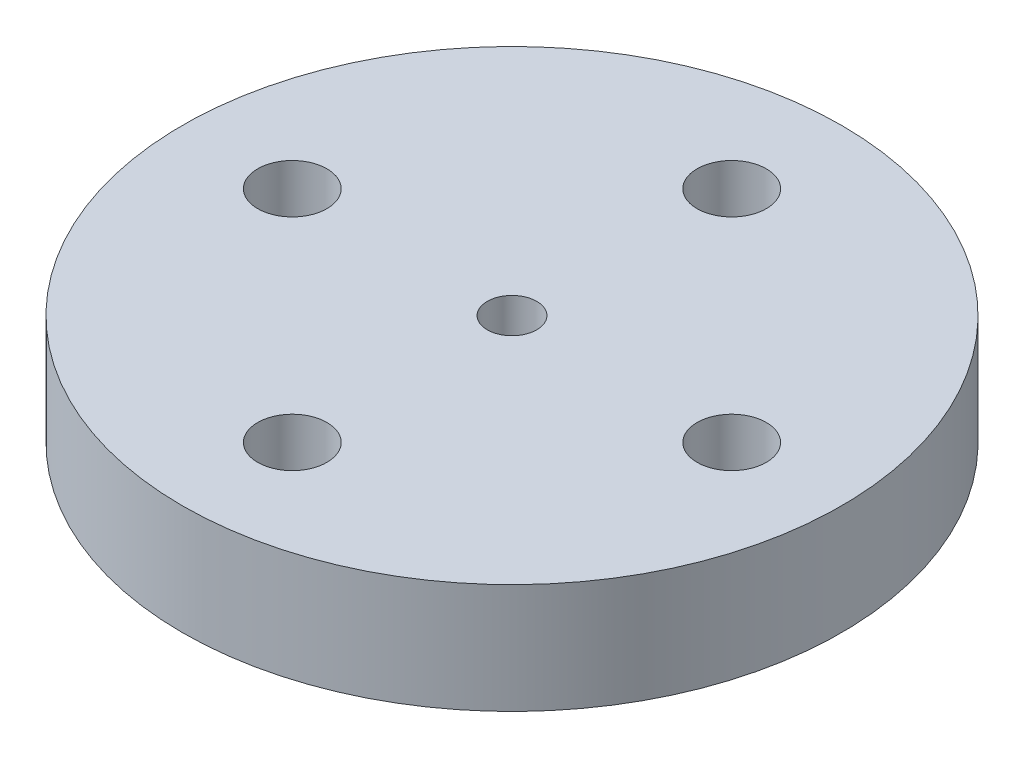
SolidWorks part; units mm, degrees
ref_plane "Alzado" through (0, 0, 0) normal (0, 0, 1) x (1, 0, 0)
ref_plane "Planta" through (0, 0, 0) normal (0, 1, 0) x (1, 0, 0)
ref_plane "Vista lateral" through (0, 0, 0) normal (1, 0, 0) x (0, 0, -1)
sketch "Sketch1" plane through (0, 0, 0) normal (0, 1, 0) x (1, 0, 0)
  circle A1 centre (0, 0) radius 30
  dimension "D1" = 60
extrude "Boss-Extrude1" add sketch "Sketch1" along normal blind 10
sketch "Sketch2" plane through (0, 10, 0) normal (0, 1, 0) x (1, 0, 0)
  line L0 (-6.2048, 3.75) -> (6.2048, 3.75)
  arc A0 (-6.2048, 3.75) -> (6.2048, 3.75) centre (0, 0) ccw
  dimension "D1" = 14.5
  dimension "D2" = 3.5
extrude "Cut-Extrude1" [suppressed] cut sketch "Sketch2" against normal blind 1.8
sketch "Sketch3" plane through (0, 10, 0) normal (0, 1, 0) x (1, 0, 0)
  circle A0 centre (0, 20) radius 3.15
  circle A1 centre (0, 0) radius 20 construction
  circle A2 centre (20, 0) radius 3.15
  circle A3 centre (0, -20) radius 3.15
  circle A4 centre (-20, 0) radius 3.15
  point P14 (0, 0)
  dimension "D1" = 6.3
  dimension "D3" = 40
  dimension "D2" = 20
  dimension "D4" = 4
extrude "Cut-Extrude2" cut sketch "Sketch3" against normal through all
sketch "Sketch4" plane through (0, 10, 0) normal (0, 1, 0) x (1, 0, 0)
  circle A0 centre (0, 0) radius 2.25
  dimension "D1" = 4.5
extrude "Cut-Extrude3" cut sketch "Sketch4" against normal blind 10
